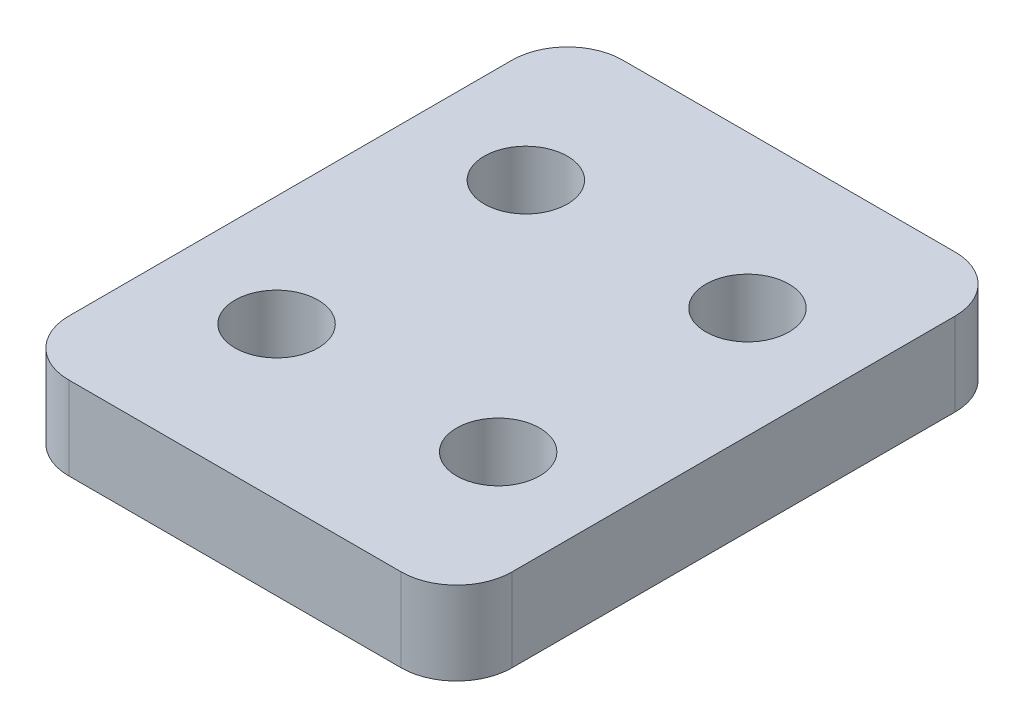
SolidWorks part; units mm, degrees
ref_plane "Plano frontal" through (0, 0, 0) normal (0, 0, 1) x (1, 0, 0)
ref_plane "Plano superior" through (0, 0, 0) normal (0, 1, 0) x (1, 0, 0)
ref_plane "Plano direito" through (0, 0, 0) normal (1, 0, 0) x (0, 0, -1)
sketch "Sketch1" plane through (0, 0, 0) normal (0, 1, 0) x (1, 0, 0)
  line L1 (-8, -10) -> (8, -10)
  line L2 (-8, -10) -> (-8, 10)
  line L3 (-8, 10) -> (8, 10)
  line L4 (8, -10) -> (8, 10)
  line L5 (-8, -10) -> (8, 10) construction
  line L6 (-8, 10) -> (8, -10) construction
  point P0 (0, 0)
  dimension "D1" = 16
  dimension "D2" = 20
extrude "Boss-Extrude1" add sketch "Sketch1" along normal mid plane 3
sketch "Sketch2" plane through (0, 1.5, 0) normal (0, 1, 0) x (1, 0, 0)
  circle A0 centre (4, -4.5) radius 1.5
  circle A1 centre (-4, -4.5) radius 1.5
  circle A2 centre (4, 4.5) radius 1.5
  circle A3 centre (-4, 4.5) radius 1.5
  dimension "D1" = 3
  dimension "D2" = 3
  dimension "D3" = 3
  dimension "D4" = 3
  dimension "D5" = 4.5
  dimension "D6" = 4.5
  dimension "D7" = 4
  dimension "D8" = 4
extrude "Cut-Extrude1" cut sketch "Sketch2" against normal blind 3 contours A1 | A3 | A2 | A0
fillet "Fillet1" radius 2 4 edges at (-8, 0, -10) (-8, 0, 10) (8, 0, 10) (8, 0, -10)
equation "\"D2@Sketch2\"=\"D1@Sketch2\""
equation "\"D3@Sketch2\"=\"D1@Sketch2\""
equation "\"D4@Sketch2\"=\"D1@Sketch2\""
equation "\"D6@Sketch2\"=\"D5@Sketch2\""
equation "\"D8@Sketch2\"=\"D7@Sketch2\""
